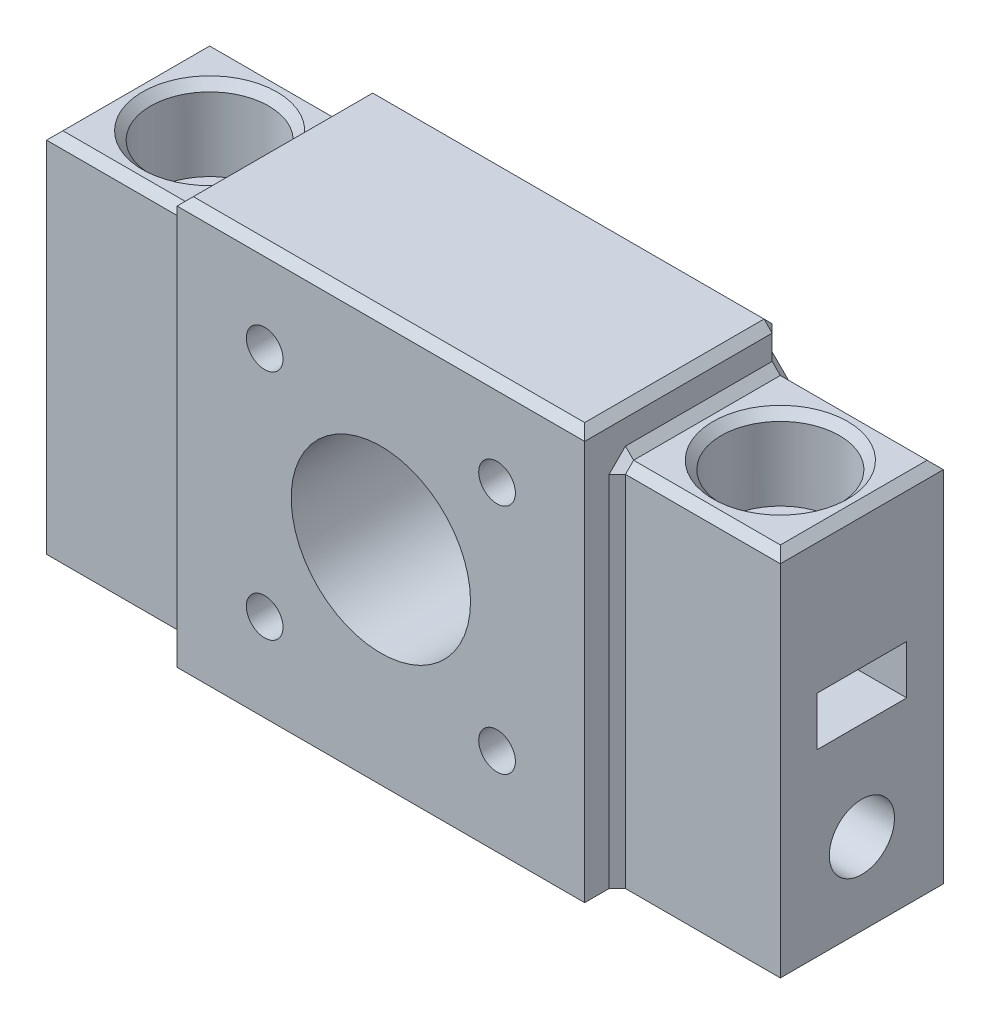
SolidWorks part; units mm, degrees
ref_plane "Front Plane" through (0, 0, 0) normal (0, 0, 1) x (1, 0, 0)
ref_plane "Top Plane" through (0, 0, 0) normal (0, 1, 0) x (1, 0, 0)
ref_plane "Right Plane" through (0, 0, 0) normal (1, 0, 0) x (0, 0, -1)
sketch "Sketch1" plane through (0, 0, 0) normal (0, 0, 1) x (1, 0, 0)
  line L1 (25, -25) -> (-25, -25)
  line L2 (25, -25) -> (25, 25) construction
  line L4 (-25, -25) -> (-25, 25) construction
  line L5 (25, -25) -> (-25, 25) construction
  line L6 (25, 25) -> (-25, -25) construction
  line L9 (0, -1000) -> (0, 49000) construction
  line L10 (-25, -25) -> (-45, -25)
  line L11 (-25, -25) -> (-25, 20) construction
  line L12 (-25, 20) -> (-45, 20)
  line L13 (-45, -25) -> (-45, 20)
  line L14 (25, -25) -> (45, -25)
  line L15 (45, -25) -> (45, 20)
  line L16 (25, 20) -> (45, 20)
  line L17 (-25, 20) -> (-25, 25)
  line L18 (25, 20) -> (25, 25)
  line L19 (-25, 25) -> (25, 25)
  circle A0 centre (0, 0) radius 11
  point P0 (0, 0)
  dimension "D3" = 22
  dimension "D2" = 50
  dimension "D5" = 20
  dimension "D6" = 45
extrude "Body" add sketch "Sketch1" along normal mid plane 20
hole_wizard "M4 Clearance Hole1" positions "Sketch7" profile "Sketch6" hole size "M4" standard "ANSI Metric" end condition through all
sketch "Sketch7" plane through (0, 0, -10) normal (0, 0, -1) x (-1, 0, 0)
  line L1 (14.25, -14.25) -> (-14.25, -14.25) construction
  line L2 (14.25, -14.25) -> (14.25, 14.25) construction
  line L3 (14.25, 14.25) -> (-14.25, 14.25) construction
  line L4 (-14.25, -14.25) -> (-14.25, 14.25) construction
  line L5 (14.25, -14.25) -> (-14.25, 14.25) construction
  line L6 (14.25, 14.25) -> (-14.25, -14.25) construction
  point P1 (0, 0)
  point P2 (-14.25, 14.25)
  point P97 (14.25, -14.25)
  point P98 (14.25, 14.25)
  point P99 (-14.25, -14.25)
  dimension "D1" = 28.5
sketch "Sketch6" plane through (0, 0, -10) normal (1, 0, 0) x (0, 1, 0)
  line L0 (0, 0) -> (0, 20)
  line L1 (0, 20) -> (2.25, 20)
  line L2 (2.25, 20) -> (2.25, 0)
  line L5 (2.25, 0) -> (0, 0)
  line L11 (0, -6.35) -> (0, 107.95) construction
  dimension "Thru Hole Dia." = 4.5
  dimension "Thru Hole Depth" = 20
sketch "Sketch10" plane through (0, 0, 10) normal (0, 0, 1) x (1, 0, 0)
  line L0 (-25, 25) -> (-25, 20) construction
  line L1 (25, -25) -> (-25, -25)
  line L2 (25, -25) -> (25, 25)
  line L3 (25, 25) -> (-25, 25)
  line L4 (-25, -25) -> (-25, 25)
  line L5 (25, -25) -> (-25, 25) construction
  line L6 (25, 25) -> (-25, -25) construction
  circle A0 centre (-14.25, -14.25) radius 2.25 construction
  circle A1 centre (14.25, -14.25) radius 2.25 construction
  circle A2 centre (14.25, 14.25) radius 2.25 construction
  circle A3 centre (0, 0) radius 11 construction
  circle A4 centre (-14.25, 14.25) radius 2.25 construction
  circle A5 centre (-14.25, -14.25) radius 2.25
  circle A6 centre (14.25, -14.25) radius 2.25
  circle A7 centre (14.25, 14.25) radius 2.25
  circle A8 centre (0, 0) radius 11
  circle A9 centre (-14.25, 14.25) radius 2.25
  point P0 (0, 0)
extrude "Elevation" add sketch "Sketch10" along normal blind 4
sketch "Sketch13" plane through (0, 0, -10) normal (0, 0, -1) x (-1, 0, 0)
  circle A0 centre (-14.25, 14.25) radius 3.75
  circle A1 centre (14.25, 14.25) radius 3.75
  circle A2 centre (14.25, -14.25) radius 3.75
  circle A3 centre (-14.25, -14.25) radius 3.75
  dimension "D1" = 7.5
extrude "M4_Screw_Place" cut sketch "Sketch13" against normal blind 4
sketch "Sketch14" plane through (0, 20, 0) normal (0, 1, 0) x (1, 0, 0)
  line L0 (-45, 10) -> (-25, -10) construction
  circle A0 centre (-35, 0) radius 7.25
  dimension "D1" = 14.5
extrude "Spring_Hole" cut sketch "Sketch14" against normal blind 10
sketch "Sketch15" plane through (-45, 0, 0) normal (-1, 0, 0) x (0, 0, 1)
  line L1 (5.5, -3) -> (-5.5, -3)
  line L2 (5.5, -3) -> (5.5, 3)
  line L3 (5.5, 3) -> (-5.5, 3)
  line L4 (-5.5, -3) -> (-5.5, 3)
  line L5 (5.5, -3) -> (-5.5, 3) construction
  line L6 (5.5, 3) -> (-5.5, -3) construction
  line L8 (10, 20) -> (-10, 20) construction
  point P0 (0, 0)
  dimension "D1" = 11
  dimension "D2" = 6
  dimension "D3" = 20
extrude "Nut_Hole" cut sketch "Sketch15" against normal blind 20
sketch "Sketch16" plane through (0, 10, 0) normal (0, 1, 0) x (1, 0, 0)
  circle A0 centre (-35, 0) radius 3.25
  dimension "D1" = 6.5
extrude "Shaft_Hole" cut sketch "Sketch16" against normal up to surface (13 mm away) up to face at (-35, -3, 0)
sketch "Sketch17" plane through (-45, 0, 0) normal (-1, 0, 0) x (0, 0, 1)
  line L0 (10, 20) -> (-10, 20) construction
  circle A0 centre (0, -15) radius 4
  dimension "D2" = 8
  dimension "D1" = 35
extrude "Brake_Screw_Hole" cut sketch "Sketch17" against normal blind 20
sketch "Sketch18" plane through (0, -25, 0) normal (0, -1, 0) x (1, 0, 0)
  line L1 (31, -5.5) -> (25, -5.5)
  line L2 (31, -5.5) -> (31, 5.5)
  line L3 (31, 5.5) -> (25, 5.5)
  line L4 (25, -5.5) -> (25, 5.5)
  line L5 (31, -5.5) -> (25, 5.5) construction
  line L6 (31, 5.5) -> (25, -5.5) construction
  line L7 (45, 10) -> (45, -10) construction
  point P0 (28, 0)
  dimension "D1" = 11
  dimension "D2" = 6
  dimension "D3" = 14
extrude "Brake_Nut_Hole" cut sketch "Sketch18" against normal up to vertex (25 mm away) up to point (0, 0, 0)
mirror "Mirror1" about plane through (0, 0, 0) normal (1, 0, 0) of "Brake_Screw_Hole", "Brake_Nut_Hole", "Shaft_Hole", "Nut_Hole", "Spring_Hole"
chamfer "Chamfer1" distance 1 angle 45 18 edges at (-25, -2.5, 10) (-25, 22.5, -10) (-25, 20, 0) (-35, 20, 10) (-45, 20, 0) (-35, 20, -10) (-42.25, 20, 0) (25, -2.5, 10) (25, 22.5, -10) (45, 20, 0) (35, 20, 10) (25, 20, 0) (35, 20, -10) (42.25, 20, 0) (25, 25, 2) (0, 25, 14) (-25, 25, 2) (0, 25, -10)
